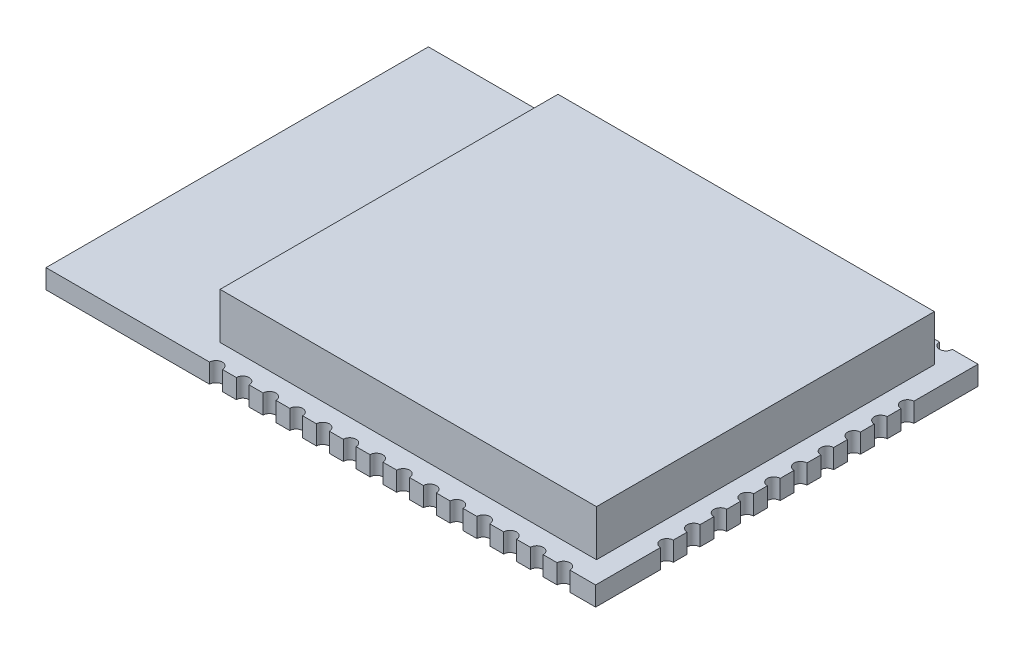
SolidWorks part; units mm, degrees
ref_plane "Front Plane" through (0, 0, 0) normal (0, 0, 1) x (1, 0, 0)
ref_plane "Top Plane" through (0, 0, 0) normal (0, 1, 0) x (1, 0, 0)
ref_plane "Right Plane" through (0, 0, 0) normal (1, 0, 0) x (0, 0, -1)
sketch "Sketch2" plane through (0, 0, 0) normal (0, 1, 0) x (1, 0, 0)
  line L1 (-12.85, -8.94) -> (12.85, -8.94)
  line L2 (-12.85, -8.94) -> (-12.85, 8.94)
  line L3 (-12.85, 8.94) -> (12.85, 8.94)
  line L4 (12.85, -8.94) -> (12.85, 8.94)
  line L5 (-12.85, -8.94) -> (12.85, 8.94) construction
  line L6 (-12.85, 8.94) -> (12.85, -8.94) construction
  point P0 (0, 0)
  dimension "D1" = 17.88
  dimension "D2" = 25.7
extrude "Boss-Extrude1" add sketch "Sketch2" along normal blind 0.9
sketch "Sketch3" plane through (0, 0.9, 0) normal (0, 1, 0) x (1, 0, 0)
  line L1 (-5.75, -7.9) -> (11.85, -7.9)
  line L2 (-5.75, -7.9) -> (-5.75, 7.9)
  line L3 (-5.75, 7.9) -> (11.85, 7.9)
  line L4 (11.85, -7.9) -> (11.85, 7.9)
  line L5 (-5.75, -7.9) -> (11.85, 7.9) construction
  line L6 (-5.75, 7.9) -> (11.85, -7.9) construction
  line L7 (12.85, -8.94) -> (12.85, 8.94) construction
  line L8 (3.05, 7.9) -> (3.05, 8.94) construction
  line L9 (12.85, 8.94) -> (-12.85, 8.94) construction
  line L10 (3.05, -7.9) -> (3.05, -8.94) construction
  line L11 (-12.85, -8.94) -> (12.85, -8.94) construction
  point P0 (3.05, 0)
  dimension "D1" = 17.6
  dimension "D2" = 15.8
  dimension "D3" = 1
extrude "Boss-Extrude2" add sketch "Sketch3" along normal blind 2.15
hole_wizard "Ø1.5mm Dowel Hole1" positions "Sketch5" profile "Sketch4" hole size "Ø1.5" standard "ANSI Metric" end condition through all
sketch "Sketch5" plane through (0, 3.05, 0) normal (0, 1, 0) x (1, 0, 0)
  line L2 (12.85, 8.94) -> (-12.85, 8.94) construction
  line L3 (12.85, -8.94) -> (12.85, 8.94) construction
  line L4 (-12.85, -8.94) -> (12.85, -8.94) construction
  point P0 (11.35, 8.94)
  point P21 (10.1, 8.94)
  point P22 (8.85, 8.94)
  point P23 (7.6, 8.94)
  point P24 (6.35, 8.94)
  point P25 (5.1, 8.94)
  point P26 (3.85, 8.94)
  point P27 (2.6, 8.94)
  point P28 (1.35, 8.94)
  point P29 (0.1, 8.94)
  point P30 (-1.15, 8.94)
  point P31 (-2.4, 8.94)
  point P32 (-3.65, 8.94)
  point P33 (-4.9, 8.94)
  point P34 (11.35, -8.94)
  point P47 (10.1, -8.94)
  point P48 (8.85, -8.94)
  point P49 (7.6, -8.94)
  point P50 (6.35, -8.94)
  point P51 (5.1, -8.94)
  point P52 (3.85, -8.94)
  point P53 (2.6, -8.94)
  point P54 (1.35, -8.94)
  point P55 (0.1, -8.94)
  point P56 (-1.15, -8.94)
  point P57 (-2.4, -8.94)
  point P58 (-3.65, -8.94)
  point P59 (-4.9, -8.94)
  point P60 (12.85, 5.64)
  point P67 (12.85, 4.39)
  point P68 (12.85, 3.14)
  point P69 (12.85, 1.89)
  point P70 (12.85, 0.64)
  point P71 (12.85, -0.61)
  point P72 (12.85, -1.86)
  point P73 (12.85, -3.11)
  point P74 (12.85, -4.36)
  point P75 (12.85, -5.61)
  dimension "D1" = 1.5
  dimension "D4" = 3.3
  dimension "D2" = 14
  dimension "D3" = 14
  dimension "D5" = 10
sketch "Sketch4" plane through (11.35, 3.05, -8.94) normal (1, 0, 0) x (0, 0, 1)
  line L0 (0, 0) -> (0, 3.05)
  line L1 (0, 3.05) -> (0.3, 3.05)
  line L2 (0.3, 3.05) -> (0.3, 0)
  line L5 (0.3, 0) -> (0, 0)
  line L11 (0, -6.35) -> (0, 107.95) construction
  dimension "Thru Hole Dia." = 0.6
  dimension "Thru Hole Depth" = 3.05
